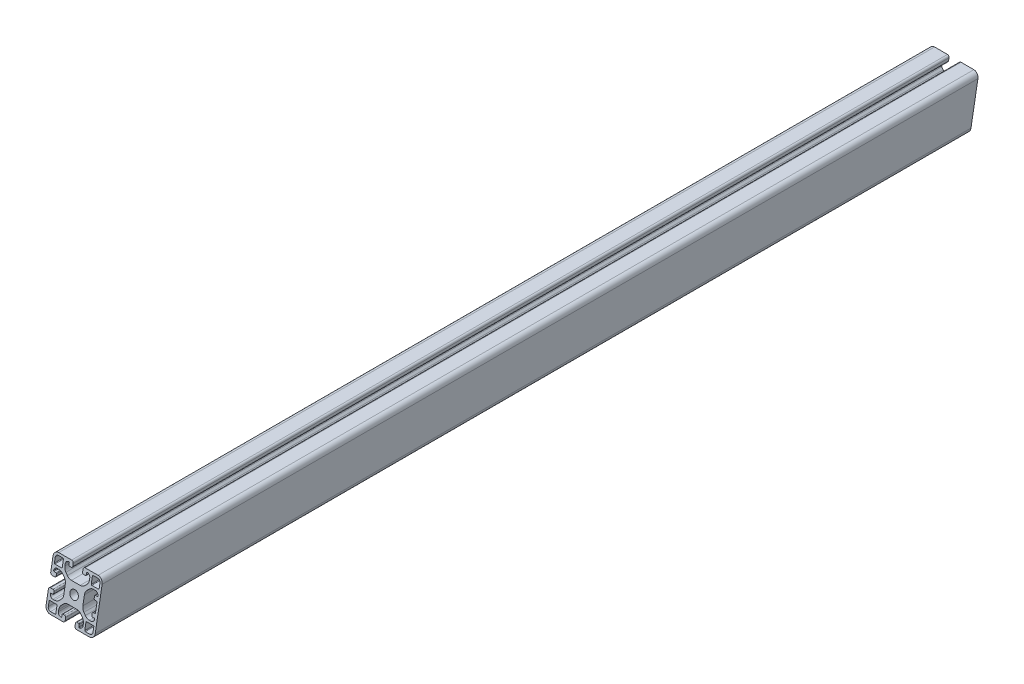
SolidWorks part; units mm, degrees
ref_plane "Piano frontale" through (0, 0, 0) normal (0, 0, 1) x (1, 0, 0)
ref_plane "Piano superiore" through (0, 0, 0) normal (0, 1, 0) x (1, 0, 0)
ref_plane "Piano destro" through (0, 0, 0) normal (1, 0, 0) x (0, 0, -1)
ref_plane "Piano1" through (0, 0, -340) normal (0, 0, -1) x (-1, 0, 0)
sketch "Schizzo1" plane through (0, 0, -340) normal (0, 0, -1) x (-1, 0, 0)
  line L0 (-12.3, -18.2) -> (-16, -18.2)
  line L1 (-18.2, -16) -> (-18.2, -12.3)
  line L2 (-17.7, -11.8) -> (-12.3, -11.8)
  line L3 (-11.8, -12.3) -> (-11.8, -17.7)
  line L4 (-11.8, 17.7) -> (-11.8, 12.3)
  line L5 (-12.3, 11.8) -> (-17.7, 11.8)
  line L6 (-18.2, 12.3) -> (-18.2, 16)
  line L7 (-16, 18.2) -> (-12.3, 18.2)
  line L8 (18.2, 16) -> (18.2, 12.3)
  line L9 (17.7, 11.8) -> (12.3, 11.8)
  line L10 (11.8, 12.3) -> (11.8, 17.7)
  line L11 (12.3, 18.2) -> (16, 18.2)
  line L12 (6.5, -15.5) -> (5, -15.5)
  line L13 (4, -16.5) -> (4, -18.5)
  line L14 (5.5, -20) -> (16, -20)
  line L15 (20, -16) -> (20, -5.5)
  line L16 (18.5, -4) -> (16.5, -4)
  line L17 (15.5, -5) -> (15.5, -6.5)
  line L18 (16, -7) -> (17.55, -7)
  line L19 (18, -7.45) -> (18, -7.5)
  line L20 (15.5, -10) -> (14.1924, -10)
  line L21 (10.6569, -8.5355) -> (9.2145, -7.0931)
  line L22 (7.75, -3.5576) -> (7.75, 3.5576)
  line L23 (9.2145, 7.0931) -> (10.6569, 8.5355)
  line L24 (14.1924, 10) -> (15.5, 10)
  line L25 (18, 7.5) -> (18, 7.45)
  line L26 (17.55, 7) -> (16, 7)
  line L27 (15.5, 6.5) -> (15.5, 5)
  line L28 (16.5, 4) -> (18.5, 4)
  line L29 (20, 5.5) -> (20, 16)
  line L30 (16, 20) -> (5.5, 20)
  line L31 (4, 18.5) -> (4, 16.5)
  line L32 (5, 15.5) -> (6.5, 15.5)
  line L33 (7, 16) -> (7, 17.55)
  line L34 (7.45, 18) -> (7.5, 18)
  line L35 (10, 15.5) -> (10, 14.1924)
  line L36 (8.5355, 10.6569) -> (7.0931, 9.2145)
  line L37 (3.5576, 7.75) -> (-3.5576, 7.75)
  line L38 (-7.0931, 9.2145) -> (-8.5355, 10.6569)
  line L39 (-10, 14.1924) -> (-10, 15.5)
  line L40 (-7.5, 18) -> (-7.45, 18)
  line L41 (-7, 17.55) -> (-7, 16)
  line L42 (-6.5, 15.5) -> (-5, 15.5)
  line L43 (-4, 16.5) -> (-4, 18.5)
  line L44 (-5.5, 20) -> (-16, 20)
  line L45 (-20, 16) -> (-20, -16)
  line L46 (-16, -20) -> (-5.5, -20)
  line L47 (-4, -18.5) -> (-4, -16.5)
  line L48 (-5, -15.5) -> (-6.5, -15.5)
  line L49 (-7, -16) -> (-7, -17.55)
  line L50 (-7.45, -18) -> (-7.5, -18)
  line L51 (-10, -15.5) -> (-10, -14.1924)
  line L52 (-8.5355, -10.6569) -> (-7.0931, -9.2145)
  line L53 (-3.5576, -7.75) -> (3.5576, -7.75)
  line L54 (7.0931, -9.2145) -> (8.5355, -10.6569)
  line L55 (10, -14.1924) -> (10, -15.5)
  line L56 (7.5, -18) -> (7.45, -18)
  line L57 (7, -17.55) -> (7, -16)
  line L58 (18.2, -12.3) -> (18.2, -16)
  line L59 (16, -18.2) -> (12.3, -18.2)
  line L60 (11.8, -17.7) -> (11.8, -12.3)
  line L61 (12.3, -11.8) -> (17.7, -11.8)
  line L62 (-16, 7) -> (-17.5, 7)
  line L63 (-15.5, 10) -> (-14.1924, 10)
  line L64 (-10.6569, 8.5355) -> (-9.2145, 7.0931)
  line L65 (-7.75, 3.5576) -> (-7.75, -3.5576)
  line L66 (-9.2145, -7.0931) -> (-10.6569, -8.5355)
  line L67 (-14.1924, -10) -> (-15.5, -10)
  line L68 (-17.5, -7) -> (-16, -7)
  line L69 (-15.5, -6.5) -> (-15.5, -5)
  line L70 (-16.5, -4) -> (-17.5, -4)
  line L71 (-18, -3.5) -> (-18, 3.5)
  line L72 (-17.5, 4) -> (-16.5, 4)
  line L73 (-15.5, 5) -> (-15.5, 6.5)
  arc A0 (-16, -18.2) -> (-18.2, -16) centre (-16, -16) cw
  arc A1 (-18.2, -12.3) -> (-17.7, -11.8) centre (-17.7, -12.3) cw
  arc A2 (-12.3, -11.8) -> (-11.8, -12.3) centre (-12.3, -12.3) cw
  arc A3 (-11.8, -17.7) -> (-12.3, -18.2) centre (-12.3, -17.7) cw
  arc A4 (-12.3, 18.2) -> (-11.8, 17.7) centre (-12.3, 17.7) cw
  arc A5 (-11.8, 12.3) -> (-12.3, 11.8) centre (-12.3, 12.3) cw
  arc A6 (-17.7, 11.8) -> (-18.2, 12.3) centre (-17.7, 12.3) cw
  arc A7 (-18.2, 16) -> (-16, 18.2) centre (-16, 16) cw
  arc A8 (16, 18.2) -> (18.2, 16) centre (16, 16) cw
  arc A9 (18.2, 12.3) -> (17.7, 11.8) centre (17.7, 12.3) cw
  arc A10 (12.3, 11.8) -> (11.8, 12.3) centre (12.3, 12.3) cw
  arc A11 (11.8, 17.7) -> (12.3, 18.2) centre (12.3, 17.7) cw
  arc A12 (5, -15.5) -> (4, -16.5) centre (5, -16.5) ccw
  arc A13 (4, -18.5) -> (5.5, -20) centre (5.5, -18.5) ccw
  arc A14 (16, -20) -> (20, -16) centre (16, -16) ccw
  arc A15 (20, -5.5) -> (18.5, -4) centre (18.5, -5.5) ccw
  arc A16 (16.5, -4) -> (15.5, -5) centre (16.5, -5) ccw
  arc A17 (15.5, -6.5) -> (16, -7) centre (16, -6.5) ccw
  arc A18 (17.55, -7) -> (18, -7.45) centre (17.55, -7.45) cw
  arc A19 (18, -7.5) -> (15.5, -10) centre (15.5, -7.5) cw
  arc A20 (14.1924, -10) -> (10.6569, -8.5355) centre (14.1924, -5) cw
  arc A21 (9.2145, -7.0931) -> (7.75, -3.5576) centre (12.75, -3.5576) cw
  arc A22 (7.75, 3.5576) -> (9.2145, 7.0931) centre (12.75, 3.5576) cw
  arc A23 (10.6569, 8.5355) -> (14.1924, 10) centre (14.1924, 5) cw
  arc A24 (15.5, 10) -> (18, 7.5) centre (15.5, 7.5) cw
  arc A25 (18, 7.45) -> (17.55, 7) centre (17.55, 7.45) cw
  arc A26 (16, 7) -> (15.5, 6.5) centre (16, 6.5) ccw
  arc A27 (15.5, 5) -> (16.5, 4) centre (16.5, 5) ccw
  arc A28 (18.5, 4) -> (20, 5.5) centre (18.5, 5.5) ccw
  arc A29 (20, 16) -> (16, 20) centre (16, 16) ccw
  arc A30 (5.5, 20) -> (4, 18.5) centre (5.5, 18.5) ccw
  arc A31 (4, 16.5) -> (5, 15.5) centre (5, 16.5) ccw
  arc A32 (6.5, 15.5) -> (7, 16) centre (6.5, 16) ccw
  arc A33 (7, 17.55) -> (7.45, 18) centre (7.45, 17.55) cw
  arc A34 (7.5, 18) -> (10, 15.5) centre (7.5, 15.5) cw
  arc A35 (10, 14.1924) -> (8.5355, 10.6569) centre (5, 14.1924) cw
  arc A36 (7.0931, 9.2145) -> (3.5576, 7.75) centre (3.5576, 12.75) cw
  arc A37 (-3.5576, 7.75) -> (-7.0931, 9.2145) centre (-3.5576, 12.75) cw
  arc A38 (-8.5355, 10.6569) -> (-10, 14.1924) centre (-5, 14.1924) cw
  arc A39 (-10, 15.5) -> (-7.5, 18) centre (-7.5, 15.5) cw
  arc A40 (-7.45, 18) -> (-7, 17.55) centre (-7.45, 17.55) cw
  arc A41 (-7, 16) -> (-6.5, 15.5) centre (-6.5, 16) ccw
  arc A42 (-5, 15.5) -> (-4, 16.5) centre (-5, 16.5) ccw
  arc A43 (-4, 18.5) -> (-5.5, 20) centre (-5.5, 18.5) ccw
  arc A44 (-16, 20) -> (-20, 16) centre (-16, 16) ccw
  arc A45 (-20, -16) -> (-16, -20) centre (-16, -16) ccw
  arc A46 (-5.5, -20) -> (-4, -18.5) centre (-5.5, -18.5) ccw
  arc A47 (-4, -16.5) -> (-5, -15.5) centre (-5, -16.5) ccw
  arc A48 (-6.5, -15.5) -> (-7, -16) centre (-6.5, -16) ccw
  arc A49 (-7, -17.55) -> (-7.45, -18) centre (-7.45, -17.55) cw
  arc A50 (-7.5, -18) -> (-10, -15.5) centre (-7.5, -15.5) cw
  arc A51 (-10, -14.1924) -> (-8.5355, -10.6569) centre (-5, -14.1924) cw
  arc A52 (-7.0931, -9.2145) -> (-3.5576, -7.75) centre (-3.5576, -12.75) cw
  arc A53 (3.5576, -7.75) -> (7.0931, -9.2145) centre (3.5576, -12.75) cw
  arc A54 (8.5355, -10.6569) -> (10, -14.1924) centre (5, -14.1924) cw
  arc A55 (10, -15.5) -> (7.5, -18) centre (7.5, -15.5) cw
  arc A56 (7.45, -18) -> (7, -17.55) centre (7.45, -17.55) cw
  arc A57 (7, -16) -> (6.5, -15.5) centre (6.5, -16) ccw
  arc A58 (17.7, -11.8) -> (18.2, -12.3) centre (17.7, -12.3) cw
  arc A59 (18.2, -16) -> (16, -18.2) centre (16, -16) cw
  arc A60 (12.3, -18.2) -> (11.8, -17.7) centre (12.3, -17.7) cw
  arc A61 (11.8, -12.3) -> (12.3, -11.8) centre (12.3, -12.3) cw
  circle A62 centre (0, 0) radius 3.4
  arc A63 (-15.5, 6.5) -> (-16, 7) centre (-16, 6.5) ccw
  arc A64 (-17.5, 7) -> (-18, 7.5) centre (-17.5, 7.5) cw
  arc A65 (-18, 7.5) -> (-15.5, 10) centre (-15.5, 7.5) cw
  arc A66 (-14.1924, 10) -> (-10.6569, 8.5355) centre (-14.1924, 5) cw
  arc A67 (-9.2145, 7.0931) -> (-7.75, 3.5576) centre (-12.75, 3.5576) cw
  arc A68 (-7.75, -3.5576) -> (-9.2145, -7.0931) centre (-12.75, -3.5576) cw
  arc A69 (-10.6569, -8.5355) -> (-14.1924, -10) centre (-14.1924, -5) cw
  arc A70 (-15.5, -10) -> (-18, -7.5) centre (-15.5, -7.5) cw
  arc A71 (-18, -7.5) -> (-17.5, -7) centre (-17.5, -7.5) cw
  arc A72 (-16, -7) -> (-15.5, -6.5) centre (-16, -6.5) ccw
  arc A73 (-15.5, -5) -> (-16.5, -4) centre (-16.5, -5) ccw
  arc A74 (-17.5, -4) -> (-18, -3.5) centre (-17.5, -3.5) cw
  arc A75 (-18, 3.5) -> (-17.5, 4) centre (-17.5, 3.5) cw
  arc A76 (-16.5, 4) -> (-15.5, 5) centre (-16.5, 5) ccw
extrude "Estrusione-Estrusione1" add sketch "Schizzo1" against normal blind 720
sketch "Schizzo9" plane through (20, 0, 0) normal (1, 0, 0) x (0, 0, -1)
  line L0 (340, -16) -> (340, 16) construction
  line L1 (-380, 16) -> (-380, -16) construction
  line L2 (340, 16) -> (340, 20) construction
  line L3 (340, 20) -> (-380, 20) construction
  line L4 (-380, 20) -> (-380, 16) construction
  line L5 (340, -20) -> (340, -16) construction
  line L6 (-380, -16) -> (-380, -20) construction
  line L7 (-380, -20) -> (340, -20) construction
  line L8 (340, -16) -> (340, 16)
  line L9 (-380, 16) -> (-380, -16)
  line L10 (340, 16) -> (340, 20)
  line L11 (340, 20) -> (-380, 20)
  line L12 (-380, 20) -> (-380, 16)
  line L13 (340, -20) -> (340, -16)
  line L14 (-380, -16) -> (-380, -20)
  line L15 (-380, -20) -> (340, -20)
  line L16 (340, 20) -> (332.9469, -20)
  line L17 (-380, -20) -> (-372.9507, 20)
extrude "Taglio-Estrusione4" cut sketch "Schizzo9" against normal through all
